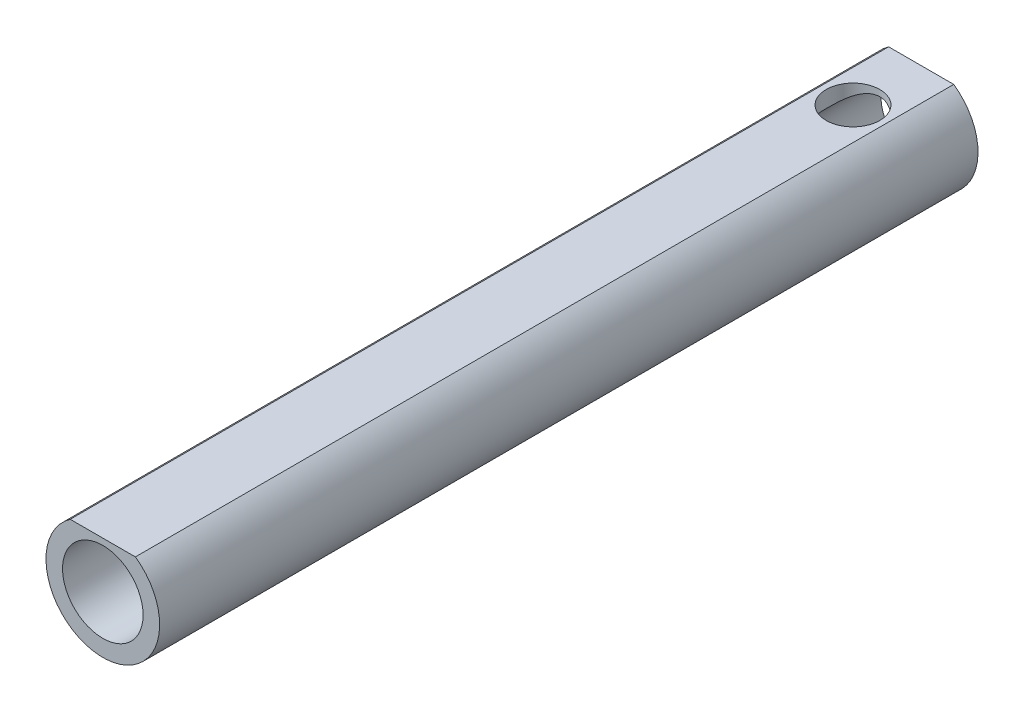
SolidWorks part; units mm, degrees
ref_plane "Front Plane" through (0, 0, 0) normal (0, 0, 1) x (1, 0, 0)
ref_plane "Top Plane" through (0, 0, 0) normal (0, 1, 0) x (1, 0, 0)
ref_plane "Right Plane" through (0, 0, 0) normal (1, 0, 0) x (0, 0, -1)
sketch "Sketch1" plane through (0, 0, 0) normal (0, 0, 1) x (1, 0, 0)
  circle A0 centre (0, 0) radius 3.175
  circle A1 centre (0, 0) radius 2.25
  dimension "D1" = 6.35
  dimension "D2" = 4.5
extrude "Boss-Extrude1" add sketch "Sketch1" along normal blind 45.72
sketch "Sketch2" plane through (0, 0, 45.72) normal (0, 0, 1) x (1, 0, 0)
  line L1 (-1.8196, 2.6018) -> (1.991, 2.6018)
  line L2 (-1.8196, 2.6018) -> (-1.8196, 5.9491)
  line L3 (-1.8196, 5.9491) -> (1.991, 5.9491)
  line L4 (1.991, 2.6018) -> (1.991, 5.9491)
  circle A0 centre (0, 0) radius 3.175 construction
extrude "Cut-Extrude1" cut sketch "Sketch2" against normal blind 48.514
sketch "Sketch3" plane through (0, 2.6018, 0) normal (0, 1, 0) x (1, 0, 0)
  line L0 (0, 0) -> (0, -45.72) construction
  line L1 (-1.8196, -45.72) -> (1.8196, -45.72) construction
  line L2 (-1.8196, 0) -> (1.8196, 0) construction
  circle A0 centre (0, -3.81) radius 1.5
  dimension "D1" = 3
  dimension "D2" = 3.81
extrude "Cut-Extrude2" cut sketch "Sketch3" against normal blind 2.54
